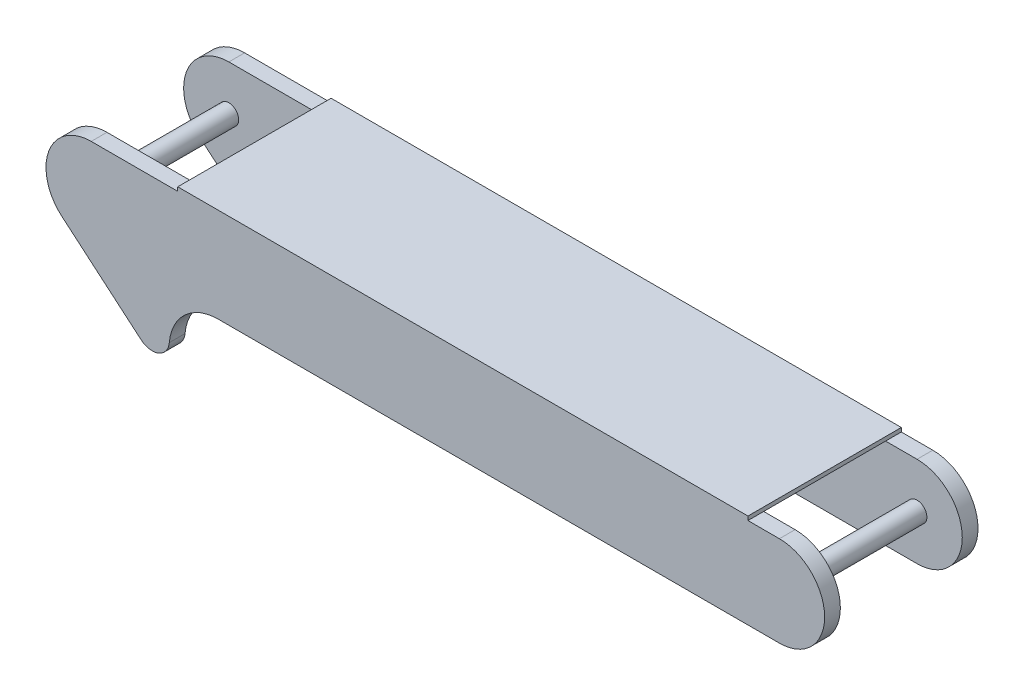
SolidWorks part; units mm, degrees
ref_plane "Alzado" through (0, 0, 0) normal (0, 0, 1) x (1, 0, 0)
ref_plane "Planta" through (0, 0, 0) normal (0, 1, 0) x (1, 0, 0)
ref_plane "Vista lateral" through (0, 0, 0) normal (1, 0, 0) x (0, 0, -1)
other "Centro de masa"
ref_plane "Plano1" through (0, 0, 39) normal (0, 0, 1) x (1, 0, 0)
sketch "Croquis1" plane through (0, 0, 39) normal (0, 0, 1) x (1, 0, 0)
  line L0 (0, 0) -> (350, 0) construction
  line L1 (-14.8827, -17.5358) -> (25.3381, -51.6712)
  line L2 (0, 23) -> (350, 23)
  line L4 (64.6164, -23) -> (350, -23)
  arc A0 (0, 23) -> (-14.8827, -17.5358) centre (0, 0) ccw
  arc A1 (350, 23) -> (350, -23) centre (350, 0) cw
  arc A2 (25.3381, -51.6712) -> (39.7154, -45.7778) centre (31, -45) ccw
  arc A3 (64.6164, -23) -> (39.7154, -45.7778) centre (64.6164, -48) ccw
  dimension "D2" = 350
  dimension "D6" = 17.5
  dimension "D8" = 50
  dimension "D1" = 46
  dimension "D3" = 31
  dimension "D4" = 45
extrude "Saliente-Extruir1" add sketch "Croquis1" against normal blind 8
ref_plane "Plano2" through (0, 0, -39) normal (0, 0, 1) x (1, 0, 0)
sketch "Croquis2" plane through (0, 0, -39) normal (0, 0, 1) x (1, 0, 0)
  line L3 (-14.8827, -17.5358) -> (25.3381, -51.6712)
  line L4 (64.6164, -23) -> (350, -23)
  line L5 (350, 23) -> (0, 23)
  line L6 (-14.8827, -17.5358) -> (25.3381, -51.6712)
  line L7 (64.6164, -23) -> (350, -23)
  line L8 (350, 23) -> (0, 23)
  arc A4 (0, 23) -> (-14.8827, -17.5358) centre (0, 0) ccw
  arc A5 (25.3381, -51.6712) -> (39.7154, -45.7778) centre (31, -45) ccw
  arc A6 (64.6164, -23) -> (39.7154, -45.7778) centre (64.6164, -48) ccw
  arc A7 (350, -23) -> (350, 23) centre (350, 0) ccw
  arc A8 (0, 23) -> (-14.8827, -17.5358) centre (0, 0) ccw
  arc A9 (25.3381, -51.6712) -> (39.7154, -45.7778) centre (31, -45) ccw
  arc A10 (64.6164, -23) -> (39.7154, -45.7778) centre (64.6164, -48) ccw
  arc A11 (350, -23) -> (350, 23) centre (350, 0) ccw
  dimension "D1" = 0
extrude "Saliente-Extruir2" add sketch "Croquis2" along normal blind 8 separate body
sketch "Croquis3" plane through (0, 23, 0) normal (0, 1, 0) x (1, 0, 0)
  line L1 (334, 39) -> (44, 39)
  line L2 (334, 39) -> (334, -39)
  line L3 (334, -39) -> (44, -39)
  line L4 (44, 39) -> (44, -39)
  line L5 (350, -39) -> (0, -39) construction
  line L6 (350, 31) -> (350, 39) construction
  line L7 (350, 39) -> (0, 39) construction
  dimension "D1" = 290
  dimension "D2" = 16
extrude "Saliente-Extruir3" add sketch "Croquis3" along normal blind 2
sketch "Croquis4" plane through (0, 0, -31) normal (0, 0, 1) x (1, 0, 0)
  circle A0 centre (0, 0) radius 5
  dimension "D1" = 10
extrude "Saliente-Extruir4" add sketch "Croquis4" along normal up to next
sketch "Croquis5" plane through (0, 0, 31) normal (0, 0, -1) x (-1, 0, 0)
  circle A0 centre (-350, 0) radius 5
  dimension "D1" = 10
extrude "Saliente-Extruir5" add sketch "Croquis5" along normal up to next
